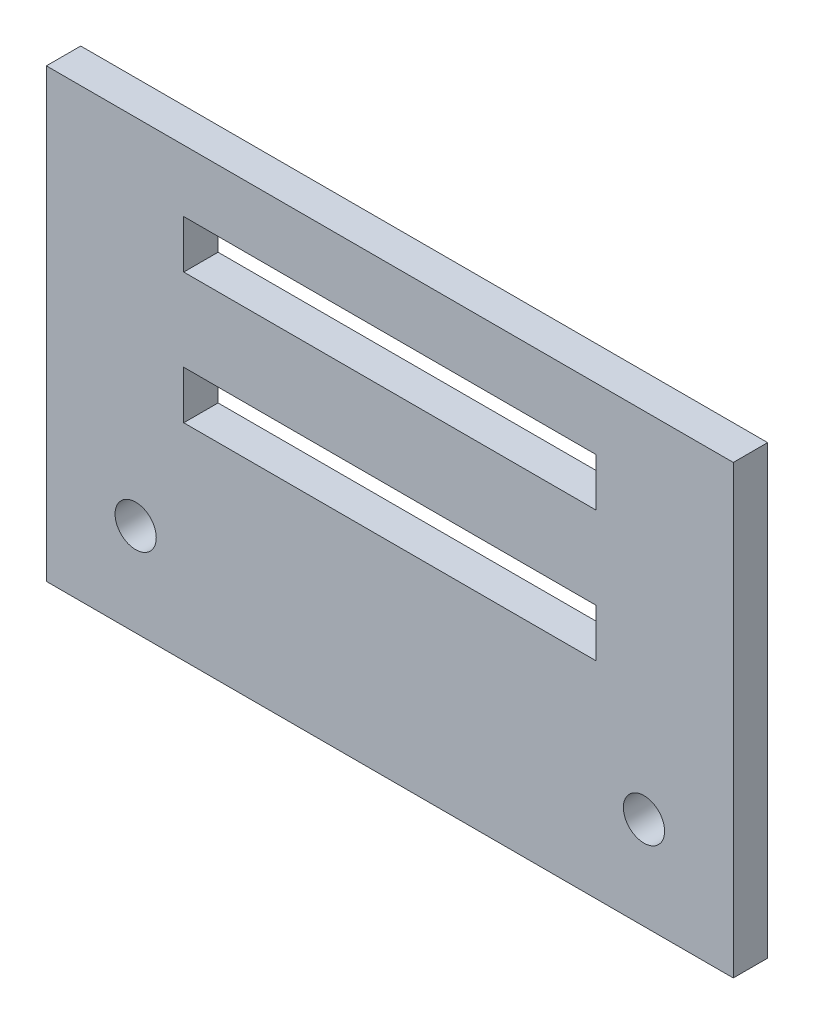
SolidWorks part; units mm, degrees
material "PBT General Purpose"
ref_plane "Front Plane" through (0, 0, 0) normal (0, 0, 1) x (1, 0, 0)
ref_plane "Top Plane" through (0, 0, 0) normal (0, 1, 0) x (1, 0, 0)
ref_plane "Right Plane" through (0, 0, 0) normal (1, 0, 0) x (0, 0, -1)
sketch "frame_outline" plane through (0, 0, 0) normal (0, 0, 1) x (1, 0, 0)
  line L123 (0.65, 0.675) -> (4.35, 0.675) construction
  line L124 (0, 0) -> (5, 0)
  line L125 (0, 0) -> (0, 3.25)
  line L126 (0, 3.25) -> (5, 3.25)
  line L127 (5, 0) -> (5, 3.25)
  line L132 (1, 1.85) -> (4, 1.85)
  line L133 (1, 1.85) -> (1, 1.5)
  line L134 (1, 1.5) -> (4, 1.5)
  line L135 (4, 1.85) -> (4, 1.5)
  line L136 (1, 2.45) -> (4, 2.45)
  line L137 (1, 2.45) -> (1, 2.8)
  line L138 (1, 2.8) -> (4, 2.8)
  line L139 (4, 2.45) -> (4, 2.8)
  circle A0 centre (0.65, 0.675) radius 0.15
  circle A1 centre (4.35, 0.675) radius 0.15
  point P12 (2.5, 1.5)
  point P13 (2.5, 0)
  point P18 (2.5, 0.675)
  point P19 (1, 1.675)
  dimension "D7" = 0.3
  dimension "D8" = 0.3
  dimension "D1" = 3
  dimension "D2" = 5
  dimension "D3" = 0.35
  dimension "D4" = 3.25
  dimension "D5" = 1.5
  dimension "D6" = 2.45
  dimension "D9" = 1.85
  dimension "D10" = 1
extrude "Boss-Extrude1" add sketch "frame_outline" along normal mid plane 0.25
equation "\"t\"= 0.25'thickness of the sheets"
equation "\"t_cf\"= 0.115'thickness of single carbon fiber layer"
equation "\"t_kapton\"= 0.025'thickness of single Kapton flex layer"
equation "\"t_fr4\"= 0.1'thickness of FR4 with copper layer"
equation "\"joint_flex\"= 0.1'Width of flextures gap"
equation "\"joint_flex_eff\"= 0.02'Width of flecture after castelation"
equation "\"joint_fold\"= 0.2'Width of folding joints for 90deg fold"
equation "\"gap_tolerance\"= 0.002'Width to have interfecence fit between carbon fiber inserts"
equation "\"assemble_angle\"= 90'Angle of assembly parts"
equation "\"D1@Boss-Extrude1\"=\"t\""
equation "\"link_lift\"= 0.5'Actuation linkage amplification for the lift motion"
equation "\"link_swing\"= 0.45'Actuation linkage amplification for the swing motion"
equation "\"D3@frame_outline\"=0.35"
